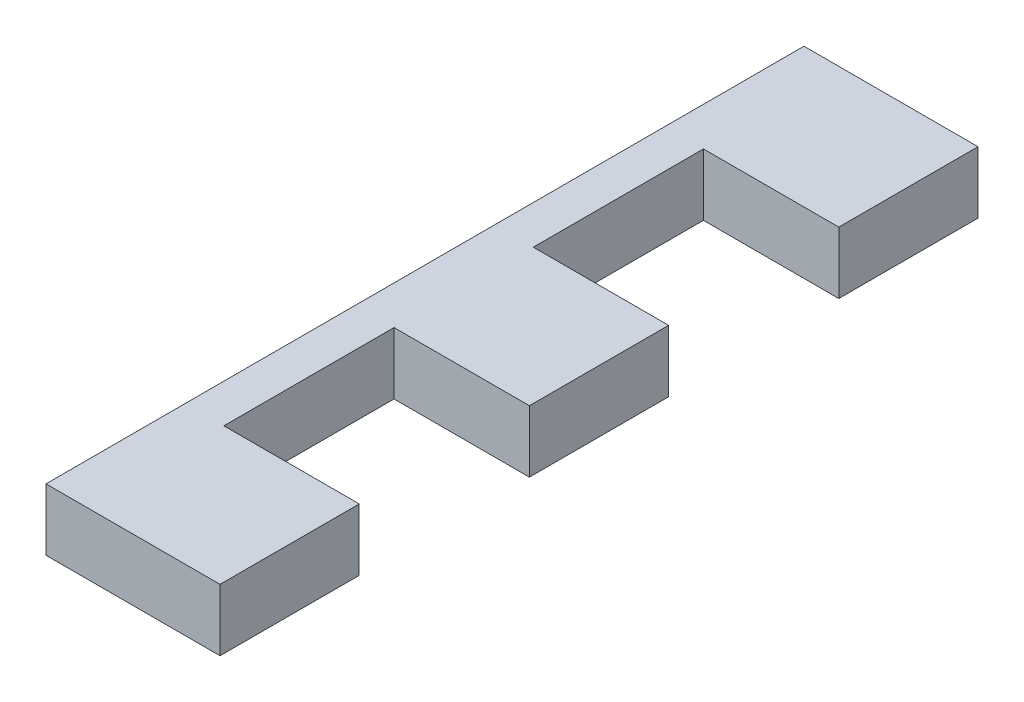
SolidWorks part; units mm, degrees
ref_plane "前视基准面" through (0, 0, 0) normal (0, 0, 1) x (1, 0, 0)
ref_plane "上视基准面" through (0, 0, 0) normal (0, 1, 0) x (1, 0, 0)
ref_plane "右视基准面" through (0, 0, 0) normal (1, 0, 0) x (0, 0, -1)
other "Configuration Table"
sketch "草图1" plane through (0, 0, 0) normal (1, 0, 0) x (0, 0, -1)
  line L0 (0, 0) -> (8, 0)
  line L1 (0, 0) -> (-8, 0)
  line L2 (-8, 0) -> (-8, 0.8)
  line L3 (-8, 0) -> (-8, -0.8)
  line L4 (0, 0) -> (0, 0.8)
  line L5 (0, 0) -> (0, -0.8)
  line L6 (8, 0) -> (8, -0.8)
  line L7 (8, 0) -> (8, 0.8)
  line L8 (8, 0.8) -> (6.2, 0.8)
  line L9 (8, 0.8) -> (9.8, 0.8)
  line L10 (0, 0.8) -> (1.8, 0.8)
  line L11 (0, 0.8) -> (-1.8, 0.8)
  line L12 (-8, 0.8) -> (-6.2, 0.8)
  line L13 (-9.8, 0.8) -> (-9.8, -0.8)
  line L14 (-8, 0.8) -> (-9.8, 0.8)
  line L15 (-9.8, -0.8) -> (-6.2, -0.8)
  line L16 (-6.2, -0.8) -> (-6.2, 0.8)
  line L17 (-1.8, 0.8) -> (-1.8, -0.8)
  line L18 (-1.8, -0.8) -> (1.8, -0.8)
  line L19 (1.8, -0.8) -> (1.8, 0.8)
  line L20 (6.2, 0.8) -> (6.2, -0.8)
  line L21 (6.2, -0.8) -> (9.8, -0.8)
  line L22 (9.8, -0.8) -> (9.8, 0.8)
extrude "凸台-拉伸1" add sketch "草图1" along normal blind 3.5 contours L13 L15 L3 L2 L14 | L15 L16 L1 L3 | L1 L16 L12 L2 | L11 L17 L1 L4 | L17 L18 L5 L1 | L18 L19 L0 L5 | L0 L19 L10 L4 | L20 L21 L6 L0 | L8 L20 L0 L7 | L21 L22 L9 L7 L6
sketch "草图2" plane through (0, 0, 0) normal (-1, 0, 0) x (0, 0, 1)
  line L1 (-9.8, 0.8) -> (9.8, 0.8)
  line L2 (-9.8, 0.8) -> (-9.8, -0.8)
  line L3 (-9.8, -0.8) -> (9.8, -0.8)
  line L4 (9.8, 0.8) -> (9.8, -0.8)
extrude "凸台-拉伸2" add sketch "草图2" along normal blind 1
